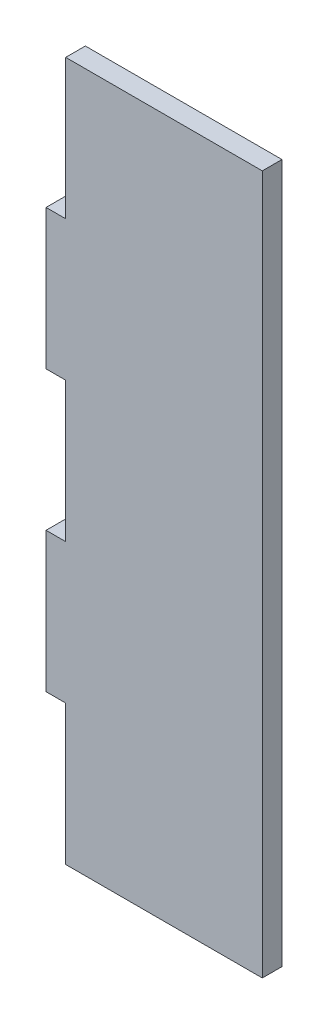
SolidWorks part; units mm, degrees
ref_plane "Front Plane" through (0, 0, 0) normal (0, 0, 1) x (1, 0, 0)
ref_plane "Top Plane" through (0, 0, 0) normal (0, 1, 0) x (1, 0, 0)
ref_plane "Right Plane" through (0, 0, 0) normal (1, 0, 0) x (0, 0, -1)
sketch "Sketch2" plane through (0, 0, 0) normal (0, 0, 1) x (1, 0, 0)
  line L0 (0, 256) -> (0, 320)
  line L1 (0, 0) -> (90, 0)
  line L2 (0, 0) -> (0, 64)
  line L3 (0, 320) -> (90, 320)
  line L4 (90, 0) -> (90, 320)
  line L5 (0, 256) -> (-9, 256)
  line L7 (0, 192) -> (-9, 192)
  line L8 (-9, 256) -> (-9, 192)
  line L9 (0, 128) -> (-9, 128)
  line L11 (0, 64) -> (-9, 64)
  line L12 (-9, 128) -> (-9, 64)
  line L13 (0, 128) -> (0, 192)
  dimension "D1" = 64
  dimension "D2" = 320
  dimension "D3" = 90
  dimension "D4" = 9
  dimension "D5" = 64
  dimension "D6" = 64
  dimension "D7" = 64
  dimension "D8" = 9
extrude "Boss-Extrude1" add sketch "Sketch2" along normal blind 9
